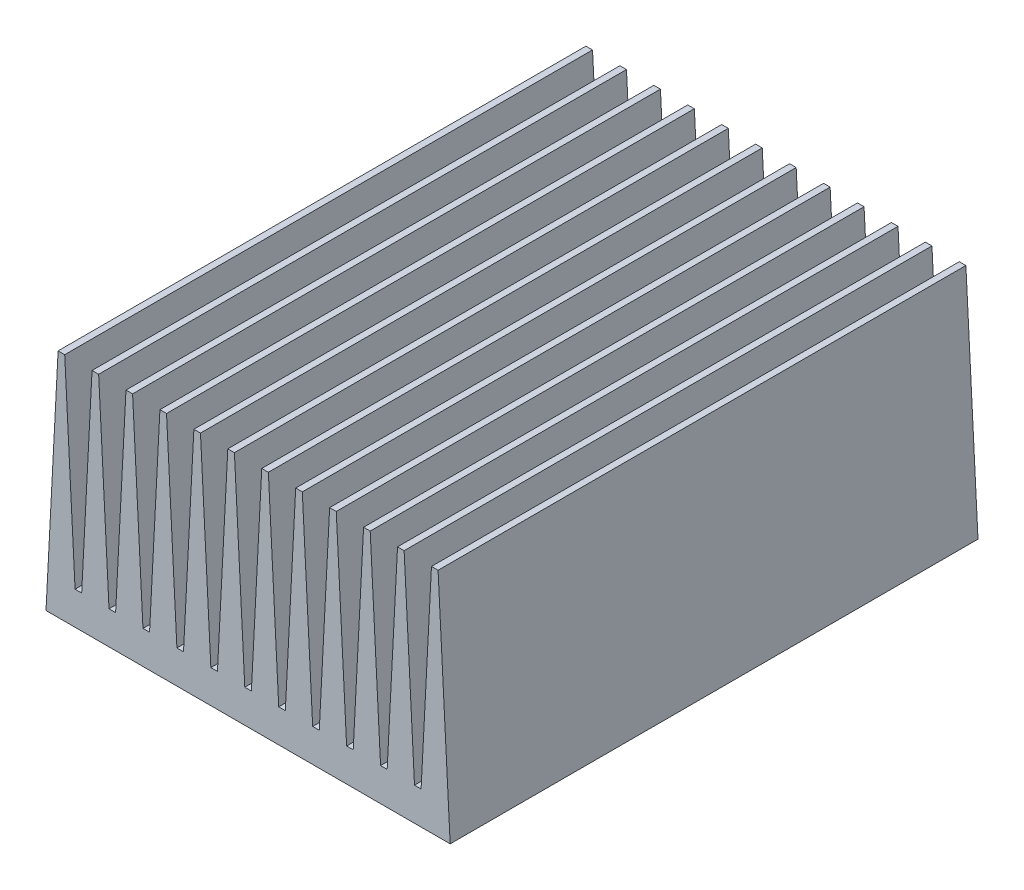
SolidWorks part; units mm, degrees
ref_plane "Front Plane" through (0, 0, 0) normal (0, 0, 1) x (1, 0, 0)
ref_plane "Top Plane" through (0, 0, 0) normal (0, 1, 0) x (1, 0, 0)
ref_plane "Right Plane" through (0, 0, 0) normal (1, 0, 0) x (0, 0, -1)
sketch "Sketch3" plane through (0, 0, 0) normal (0, 0, 1) x (1, 0, 0)
  line L0 (0, 5) -> (0.5, 5)
  line L1 (0, -19.25) -> (0, 19.25) construction
  line L2 (0.5, 5) -> (2.0722, 35)
  line L3 (2.0722, 35) -> (3.0722, 35)
  line L4 (3.0722, 35) -> (4.6445, 5)
  line L5 (4.6445, 5) -> (5.6445, 5)
  line L7 (3.1045, 0) -> (-3.1045, 0) construction
  line L8 (5.6445, 0) -> (0, 0)
  line L9 (0, 0) -> (0, 5)
  line L10 (2.5722, 35) -> (2.5722, 0) construction
  line L11 (5.6445, 5) -> (7.2167, 35)
  line L12 (7.2167, 35) -> (8.2167, 35)
  line L13 (8.2167, 35) -> (9.7889, 5)
  line L14 (9.7889, 5) -> (10.7889, 5)
  line L15 (10.7889, 5) -> (12.3612, 35)
  line L16 (12.3612, 35) -> (13.3612, 35)
  line L17 (13.3612, 35) -> (14.9334, 5)
  line L18 (14.9334, 5) -> (15.9334, 5)
  line L19 (15.9334, 5) -> (17.5056, 35)
  line L20 (17.5056, 35) -> (18.5056, 35)
  line L21 (18.5056, 35) -> (20.0779, 5)
  line L22 (20.0779, 5) -> (21.0779, 5)
  line L23 (21.0779, 5) -> (22.6501, 35)
  line L24 (22.6501, 35) -> (23.6501, 35)
  line L25 (23.6501, 35) -> (25.2223, 5)
  line L26 (25.2223, 5) -> (26.2223, 5)
  line L27 (26.2223, 5) -> (27.7946, 35)
  line L28 (27.7946, 35) -> (28.7946, 35)
  line L29 (28.7946, 35) -> (30.3668, 5)
  line L30 (30.3668, 5) -> (30.6288, 0)
  line L31 (30.3668, 5) -> (31.3668, 5) [skipped]
  line L32 (5.6445, 0) -> (30.6288, 0)
  dimension "D1" = 0.5
  dimension "D2" = 1
  dimension "D3" = 1
  dimension "D4" = 93
  dimension "D5" = 87
  dimension "D6" = 5
  dimension "D7" = 35
  dimension "D8" = 6
  dimension "D9" = 5
extrude "Boss-Extrude1" add sketch "Sketch3" against normal blind 80
mirror "Mirror1" about plane through (0, 0, 0) normal (1, 0, 0) of "Boss-Extrude1"
